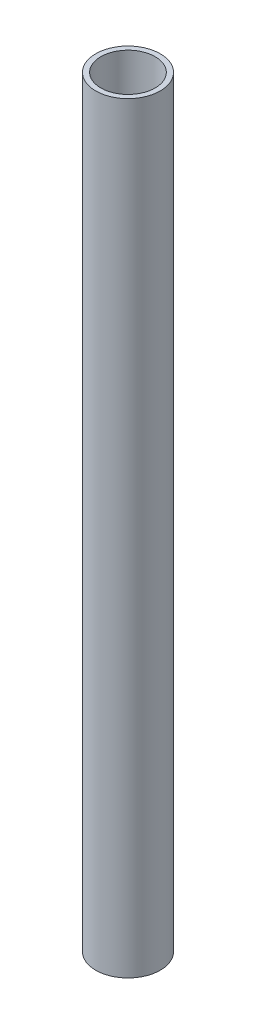
SolidWorks part; units mm, degrees
ref_plane "Front Plane" through (0, 0, 0) normal (0, 0, 1) x (1, 0, 0)
ref_plane "Top Plane" through (0, 0, 0) normal (0, 1, 0) x (1, 0, 0)
ref_plane "Right Plane" through (0, 0, 0) normal (1, 0, 0) x (0, 0, -1)
sketch "Sketch1" plane through (0, 0, 0) normal (0, 1, 0) x (1, 0, 0)
  circle A0 centre (0, 0) radius 12.7
  circle A1 centre (0, 0) radius 10.7
  dimension "D1" = 2
  dimension "D2" = 25.4
extrude "Boss-Extrude1" add sketch "Sketch1" along normal blind 300
